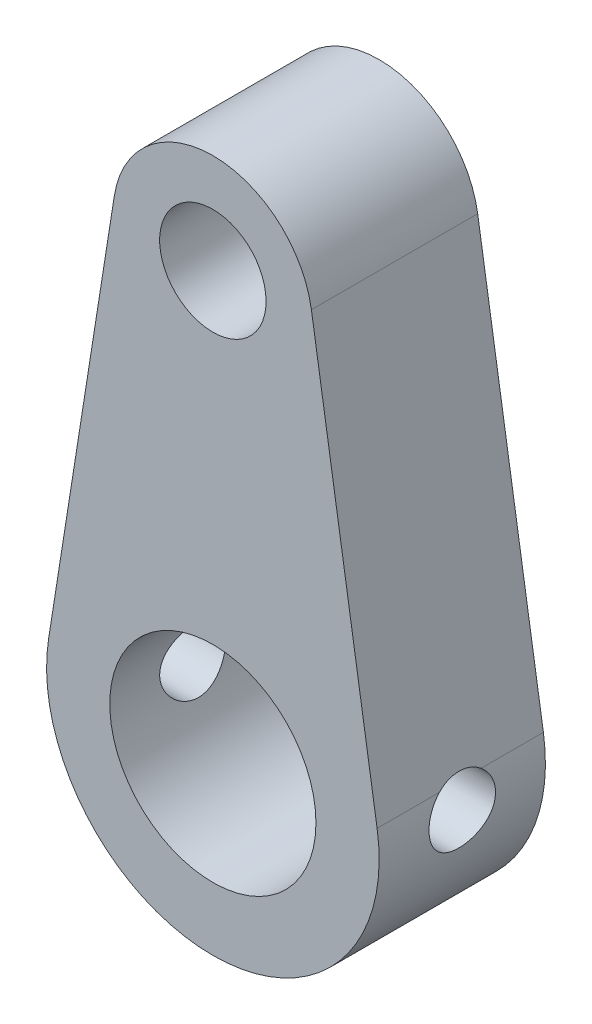
SolidWorks part; units mm, degrees
ref_plane "Alzado" through (0, 0, 0) normal (0, 0, 1) x (1, 0, 0)
ref_plane "Planta" through (0, 0, 0) normal (0, 1, 0) x (1, 0, 0)
ref_plane "Vista lateral" through (0, 0, 0) normal (1, 0, 0) x (0, 0, -1)
sketch "Croquis1" plane through (0, 0, 0) normal (0, 0, 1) x (1, 0, 0)
  line L0 (-4.9389, 0.7794) -> (-2.9633, 13.2977)
  line L2 (2.9633, 13.2977) -> (4.9389, 0.7794)
  arc A0 (-4.9389, 0.7794) -> (4.9389, 0.7794) centre (0, 0) ccw
  arc A1 (2.9633, 13.2977) -> (-2.9633, 13.2977) centre (0, 12.83) ccw
  circle A2 centre (0, 0) radius 3.1
  circle A3 centre (0, 12.83) radius 1.6
  dimension "D1" = 10
  dimension "D2" = 6.2
  dimension "D3" = 3
  dimension "D5" = 3.2
  dimension "D4" = 12.83
extrude "Saliente-Extruir1" add sketch "Croquis1" along normal blind 5
ref_plane "Plano1" through (0, 0, 0) normal (1, 0, 0) x (0, 0, -1)
sketch "Croquis3" plane through (0, 0, 0) normal (1, 0, 0) x (0, 0, -1)
  line L0 (-5, 0.7794) -> (-5, -5) construction
  line L2 (-5, -3.1) -> (0, -3.1) construction
  line L3 (-5, 3.1) -> (-5, -3.1) construction
  line L4 (-5, 13.2977) -> (-5, 0.7794) construction
  line L5 (-5, 3.1) -> (-5, -3.1) construction
  line L6 (0, -3.1) -> (0, 3.1) construction
  circle A0 centre (-2.5, 0) radius 1
  point P12 (0, 0)
  point P13 (-5, 0)
  point P14 (0, 0)
  point P15 (0, -3.1)
  point P18 (0, 0)
  point P19 (-2.5, -3.1)
  dimension "D2" = 2
  dimension "D1" = 2.5
  dimension "D3" = 3.1
extrude "Cortar-Extruir1" cut sketch "Croquis3" against normal through all both and the other way through all
